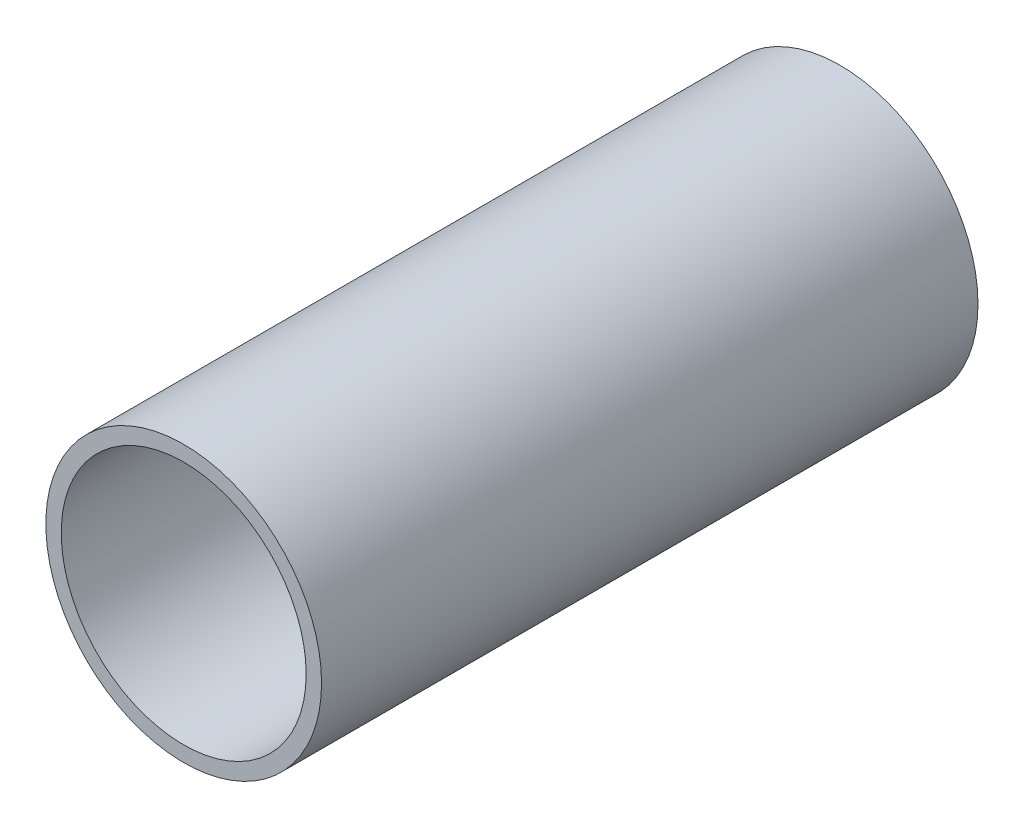
SolidWorks part; units mm, degrees
ref_plane "Plan de face" through (0, 0, 0) normal (0, 0, 1) x (1, 0, 0)
ref_plane "Plan de dessus" through (0, 0, 0) normal (0, 1, 0) x (1, 0, 0)
ref_plane "Plan de droite" through (0, 0, 0) normal (1, 0, 0) x (0, 0, -1)
sketch "Esquisse2" plane through (0, 0, 0) normal (0, 0, 1) x (1, 0, 0)
  circle A1 centre (0, 0) radius 21
  circle A2 centre (0, 0) radius 18.6558
extrude "Boss.-Extru.2" add sketch "Esquisse2" along normal blind 100
